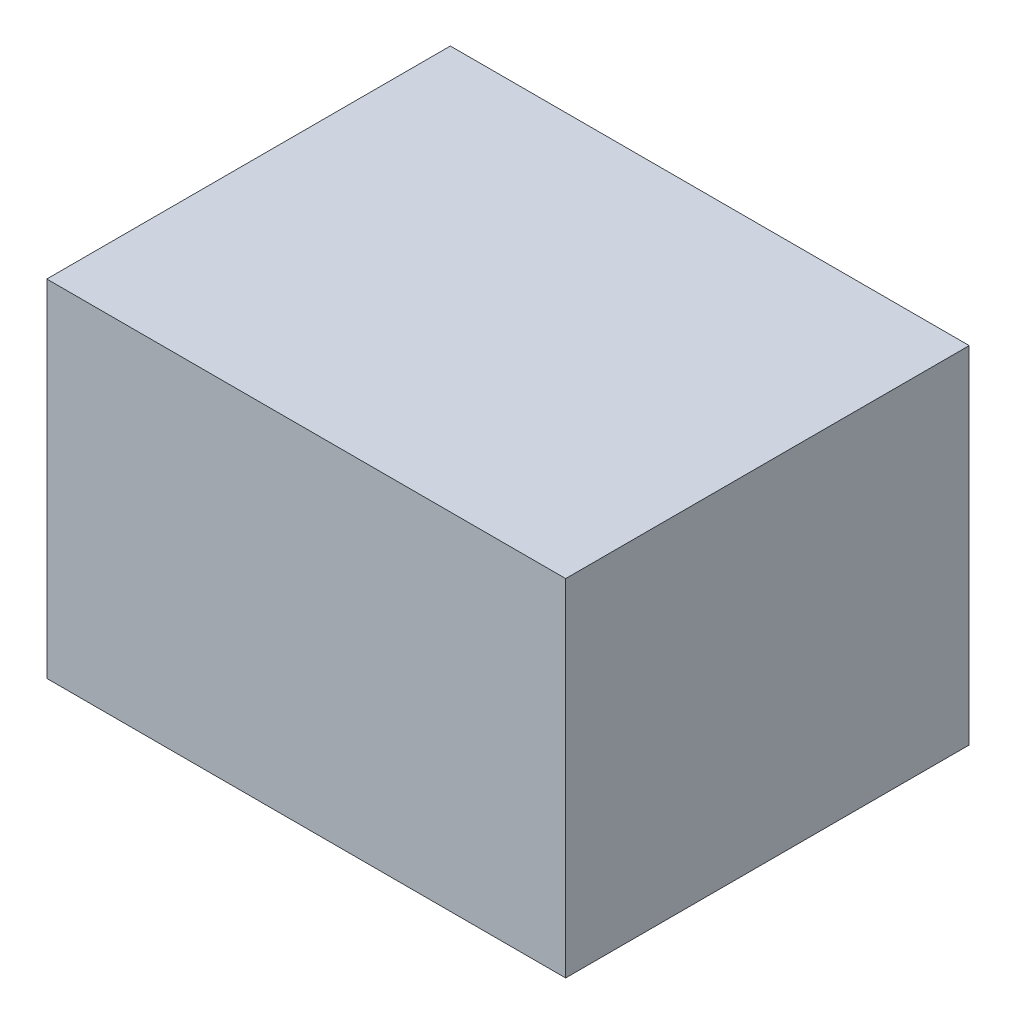
SolidWorks part; units mm, degrees
ref_plane "Plan de face" through (0, 0, 0) normal (0, 0, 1) x (1, 0, 0)
ref_plane "Plan de dessus" through (0, 0, 0) normal (0, 1, 0) x (1, 0, 0)
ref_plane "Plan de droite" through (0, 0, 0) normal (1, 0, 0) x (0, 0, -1)
sketch "Esquisse1" plane through (0, 0, 0) normal (0, 0, 1) x (1, 0, 0)
  line L1 (-22.5, -15) -> (22.5, -15)
  line L2 (-22.5, -15) -> (-22.5, 15)
  line L3 (-22.5, 15) -> (22.5, 15)
  line L4 (22.5, -15) -> (22.5, 15)
  line L5 (-22.5, -15) -> (22.5, 15) construction
  line L6 (-22.5, 15) -> (22.5, -15) construction
  point P0 (0, 0)
  dimension "D1" = 30
  dimension "D2" = 45
extrude "Boss.-Extru.1" add sketch "Esquisse1" along normal blind 35 contours L3 L4 L1 L2
